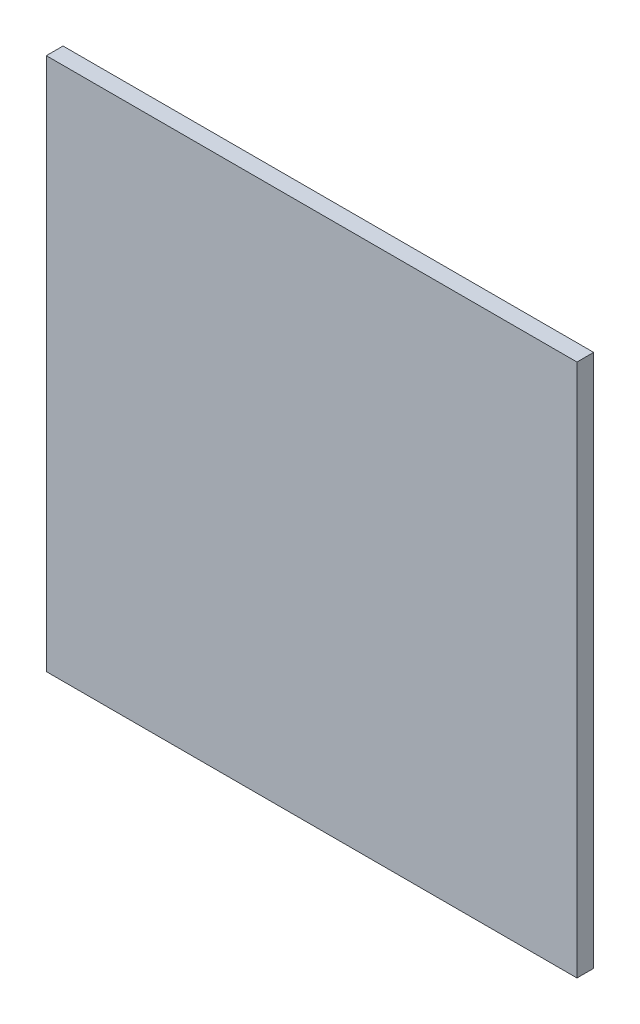
SolidWorks part; units mm, degrees
ref_plane "Front Plane" through (0, 0, 0) normal (0, 0, 1) x (1, 0, 0)
ref_plane "Top Plane" through (0, 0, 0) normal (0, 1, 0) x (1, 0, 0)
ref_plane "Right Plane" through (0, 0, 0) normal (1, 0, 0) x (0, 0, -1)
sketch "Sketch2" plane through (0, 0, 0) normal (0, 0, 1) x (1, 0, 0)
  line L1 (-40.5474, 24.0514) -> (54.6508, 24.0514)
  line L2 (-40.5474, 24.0514) -> (-40.5474, -71.6505)
  line L3 (-40.5474, -71.6505) -> (54.6508, -71.6505)
  line L4 (54.6508, 24.0514) -> (54.6508, -71.6505)
extrude "Boss-Extrude1" add sketch "Sketch2" along normal blind 3
